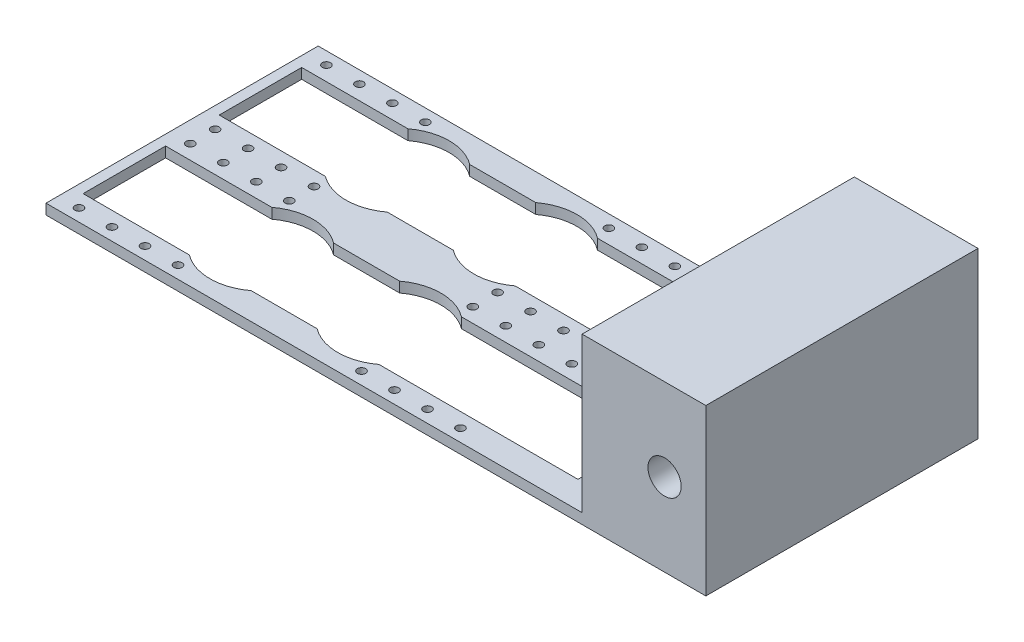
SolidWorks part; units mm, degrees
ref_plane "Front Plane" through (0, 0, 0) normal (0, 0, 1) x (1, 0, 0)
ref_plane "Top Plane" through (0, 0, 0) normal (0, 1, 0) x (1, 0, 0)
ref_plane "Right Plane" through (0, 0, 0) normal (1, 0, 0) x (0, 0, -1)
sketch "Sketch1" plane through (0, 0, 0) normal (0, 1, 0) x (1, 0, 0)
  line L1 (-80, 33) -> (80, 33)
  line L2 (-80, 33) -> (-80, -33)
  line L3 (-80, -33) -> (80, -33)
  line L4 (80, 33) -> (80, -33)
  line L5 (-80, 33) -> (80, -33) construction
  line L6 (-80, -33) -> (80, 33) construction
  point P0 (0, 0)
  dimension "D1" = 160
  dimension "D2" = 66
extrude "Boss-Extrude1" add sketch "Sketch1" along normal blind 40
sketch "Sketch2" plane through (0, 0, 33) normal (0, 0, 1) x (1, 0, 0)
  line L0 (80, 40) -> (80, 0) construction
  line L1 (-80, 40) -> (80, 40) construction
  line L2 (-80, 40) -> (50, 40)
  line L3 (-80, 40) -> (-80, 2.5)
  line L4 (-80, 2.5) -> (50, 2.5)
  line L5 (50, 40) -> (50, 2.5)
  line L6 (-80, 40) -> (50, 2.5) construction
  line L7 (-80, 2.5) -> (50, 40) construction
  line L8 (-80, 40) -> (-80, 0) construction
  circle A0 centre (70, 20) radius 4.025
  point P4 (80, 20)
  point P5 (-15, 21.25)
  dimension "D1" = 8.05
  dimension "D2" = 10
  dimension "D3" = 37.5
  dimension "D4" = 130
extrude "Cut-Extrude1" cut sketch "Sketch2" against normal through all
sketch "Sketch3" plane through (0, 40, 0) normal (0, 1, 0) x (1, 0, 0)
  line L0 (-80, 33) -> (-80, -33) construction
  line L1 (80, 33) -> (50, 33) construction
  line L2 (-75, 30) -> (-67, 30) construction
  line L3 (-75, 3) -> (-67, 3) construction
  line L4 (0, 0) -> (13.7346, 0) construction
  line L5 (-80, 33) -> (-80, -33) construction
  line L6 (-6.5, 30) -> (1.5, 30) construction
  line L7 (-75, 30) -> (-75, 3) construction
  line L8 (-77.5, 26.5) -> (42.5, 26.5)
  line L9 (-77.5, 26.5) -> (-77.5, 6.5)
  line L10 (-77.5, 6.5) -> (42.5, 6.5)
  line L11 (42.5, 26.5) -> (42.5, 6.5)
  line L12 (-6.5, 3) -> (1.5, 3) construction
  line L13 (-6.5, -3) -> (1.5, -3) construction
  line L14 (-75, -30) -> (-75, -3) construction
  line L15 (-6.5, -30) -> (1.5, -30) construction
  line L16 (-75, -3) -> (-67, -3) construction
  line L17 (-75, -30) -> (-67, -30) construction
  line L18 (42.5, -26.5) -> (42.5, -6.5)
  line L19 (-77.5, -6.5) -> (42.5, -6.5)
  line L20 (-77.5, -26.5) -> (-77.5, -6.5)
  line L21 (-77.5, -26.5) -> (42.5, -26.5)
  circle A0 centre (-75, 30) radius 1
  circle A1 centre (-75, 3) radius 1
  circle A2 centre (-67, 30) radius 1
  circle A3 centre (-59, 30) radius 1
  circle A4 centre (-51, 30) radius 1
  circle A11 centre (-67, 3) radius 1
  circle A12 centre (-59, 3) radius 1
  circle A13 centre (-51, 3) radius 1
  circle A50 centre (-6.5, 30) radius 1
  circle A51 centre (-6.5, 3) radius 1
  circle A52 centre (1.5, 30) radius 1
  circle A53 centre (9.5, 30) radius 1
  circle A54 centre (17.5, 30) radius 1
  circle A55 centre (1.5, 3) radius 1
  circle A56 centre (9.5, 3) radius 1
  circle A57 centre (17.5, 3) radius 1
  circle A58 centre (17.5, -3) radius 1
  circle A59 centre (9.5, -3) radius 1
  circle A60 centre (1.5, -3) radius 1
  circle A61 centre (17.5, -30) radius 1
  circle A62 centre (9.5, -30) radius 1
  circle A63 centre (1.5, -30) radius 1
  circle A64 centre (-6.5, -3) radius 1
  circle A65 centre (-6.5, -30) radius 1
  circle A66 centre (-51, -3) radius 1
  circle A67 centre (-59, -3) radius 1
  circle A68 centre (-67, -3) radius 1
  circle A69 centre (-51, -30) radius 1
  circle A70 centre (-59, -30) radius 1
  circle A71 centre (-67, -30) radius 1
  circle A72 centre (-75, -3) radius 1
  circle A73 centre (-75, -30) radius 1
  point P96 (-77.5, 16.5)
  point P97 (-75, 16.5)
  dimension "D1" = 2
  dimension "D3" = 3
  dimension "D4" = 27
  dimension "D12" = 2
  dimension "D2" = 5
  dimension "D6" = 8
  dimension "D8" = 8
  dimension "D9" = 20
  dimension "D10" = 120
  dimension "D11" = 2.5
  dimension "D13" = 44.5
  dimension "D15" = 8
  dimension "D17" = 8
  dimension "D5" = 4
  dimension "D7" = 4
  dimension "D14" = 4
  dimension "D16" = 4
extrude "Cut-Extrude2" cut sketch "Sketch3" against normal through all
sketch "Sketch4" plane through (0, 2.5, 0) normal (0, 1, 0) x (1, 0, 0)
  line L1 (-77.5, -6.5) -> (42.5, -6.5) construction
  line L2 (-77.5, 26.5) -> (42.5, 26.5) construction
  circle A0 centre (-44.25, -16.5) radius 12.5
  circle A1 centre (-51, -3) radius 1 construction
  circle A2 centre (-44.25, 16.5) radius 12.5
  circle A3 centre (-13.25, 16.5) radius 12.5
  circle A4 centre (-13.25, -16.5) radius 12.5
  circle A5 centre (-6.5, -3) radius 1 construction
  dimension "D1" = 25
  dimension "D4" = 6.75
  dimension "D2" = 6.75
  dimension "D3" = 10
  dimension "D5" = 10
extrude "Cut-Extrude3" cut sketch "Sketch4" against normal through all
